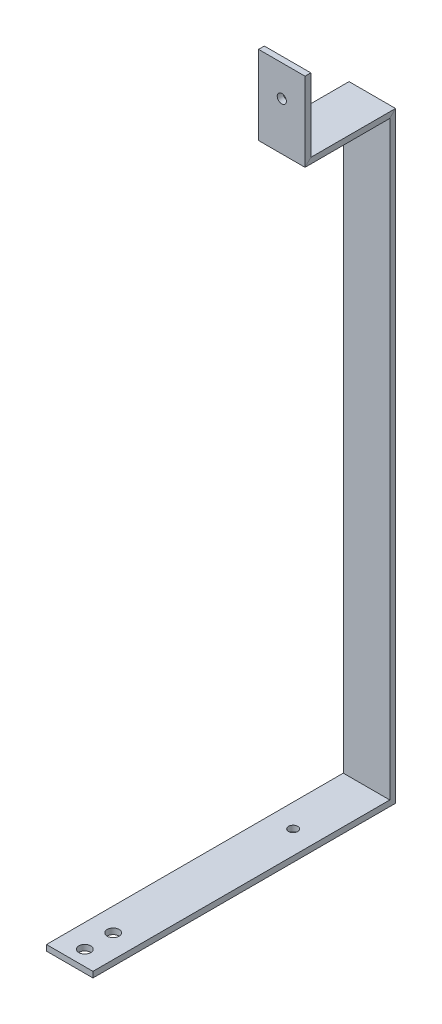
SolidWorks part; units mm, degrees
ref_plane "Alzado" through (0, 0, 0) normal (0, 0, 1) x (1, 0, 0)
ref_plane "Planta" through (0, 0, 0) normal (0, 1, 0) x (1, 0, 0)
ref_plane "Vista lateral" through (0, 0, 0) normal (1, 0, 0) x (0, 0, -1)
sketch "Croquis1" plane through (0, 0, 0) normal (0, 0, 1) x (1, 0, 0)
  line L1 (-25.4, 3.155) -> (25.4, 3.155)
  line L2 (-25.4, 3.155) -> (-25.4, -3.155)
  line L3 (-25.4, -3.155) -> (25.4, -3.155)
  line L4 (25.4, 3.155) -> (25.4, -3.155)
  line L5 (-25.4, 3.155) -> (25.4, -3.155) construction
  line L6 (-25.4, -3.155) -> (25.4, 3.155) construction
  point P0 (0, 0)
  dimension "D1" = 50.8
  dimension "D2" = 6.31
extrude "Saliente-Extruir1" add sketch "Croquis1" along normal blind 330.7
sketch "Croquis3" plane through (0, -3.155, 0) normal (0, -1, 0) x (1, 0, 0)
  line L0 (-25.4, 330.7) -> (-25.4, 0) construction
  line L1 (25.4, 0) -> (-25.4, 0)
  line L2 (25.4, 0) -> (25.4, 6.31)
  line L3 (25.4, 6.31) -> (-25.4, 6.31)
  line L4 (-25.4, 0) -> (-25.4, 6.31)
  line L5 (25.4, 0) -> (-25.4, 6.31) construction
  line L6 (25.4, 6.31) -> (-25.4, 0) construction
  line L7 (25.4, 330.7) -> (25.4, 0) construction
  line L8 (-25.4, 0) -> (25.4, 0) construction
  point P0 (0, 3.155)
  dimension "D1" = 6.31
extrude "Saliente-Extruir2" add sketch "Croquis3" against normal blind 644.51
sketch "Croquis4" plane through (0, 641.355, 0) normal (0, 1, 0) x (1, 0, 0)
  line L0 (25.4, -6.31) -> (-25.4, -6.31)
  line L1 (-25.4, -6.31) -> (-25.4, 0)
  line L2 (-25.4, 0) -> (25.4, 0)
  line L3 (25.4, 0) -> (25.4, -6.31)
  line L4 (0, 0) -> (0, -6.31) construction
  line L5 (0, -6.31) -> (0, -3.155) construction
  line L6 (0, -3.155) -> (-25.4, -3.155) construction
sketch3d "Croquis3D1"
  line L0 (0, 641.355, 3.155) -> (0, 651.355, 3.155)
  line L2 (0, 651.355, 3.155) -> (0, 651.355, 95.765)
  line L3 (0, 651.355, 95.765) -> (0, 734.515, 95.765)
  dimension "D1" = 10
  dimension "D2" = 92.61
  dimension "D3" = 83.16
sweep "Barrer1" add profiles "Croquis4" path "Croquis3D1"
sketch "Croquis8" plane through (0, -3.155, 0) normal (0, -1, 0) x (1, 0, 0)
  line L0 (0, 330.7) -> (0, 314.2) construction
  line L1 (-25.4, 330.7) -> (25.4, 330.7) construction
  line L2 (0, 314.2) -> (0, 283.2) construction
  circle A0 centre (0, 314.2) radius 6.5
  circle A1 centre (0, 283.2) radius 6.5
  dimension "D3" = 13
  dimension "D4" = 13
  dimension "D1" = 16.5
  dimension "D2" = 31
extrude "Cortar-Extruir2" cut sketch "Croquis8" against normal blind 10
sketch "Croquis10" plane through (0, 0, 98.92) normal (0, 0, 1) x (1, 0, 0)
  line L0 (0, 734.515) -> (0, 700.515) construction
  line L1 (-25.4, 734.515) -> (25.4, 734.515) construction
  line L2 (0, 651.355) -> (0, 734.515) construction
  circle A0 centre (0, 700.515) radius 5
  dimension "D1" = 10
  dimension "D2" = 34
extrude "Cortar-Extruir4" cut sketch "Croquis10" against normal blind 50
sketch "Croquis11" plane through (0, -3.155, 0) normal (0, -1, 0) x (1, 0, 0)
  line L0 (0, 0) -> (0, 86.51) construction
  circle A0 centre (0, 86.51) radius 5
  dimension "D2" = 10
  dimension "D1" = 86.51
extrude "Cortar-Extruir5" cut sketch "Croquis11" against normal blind 10
